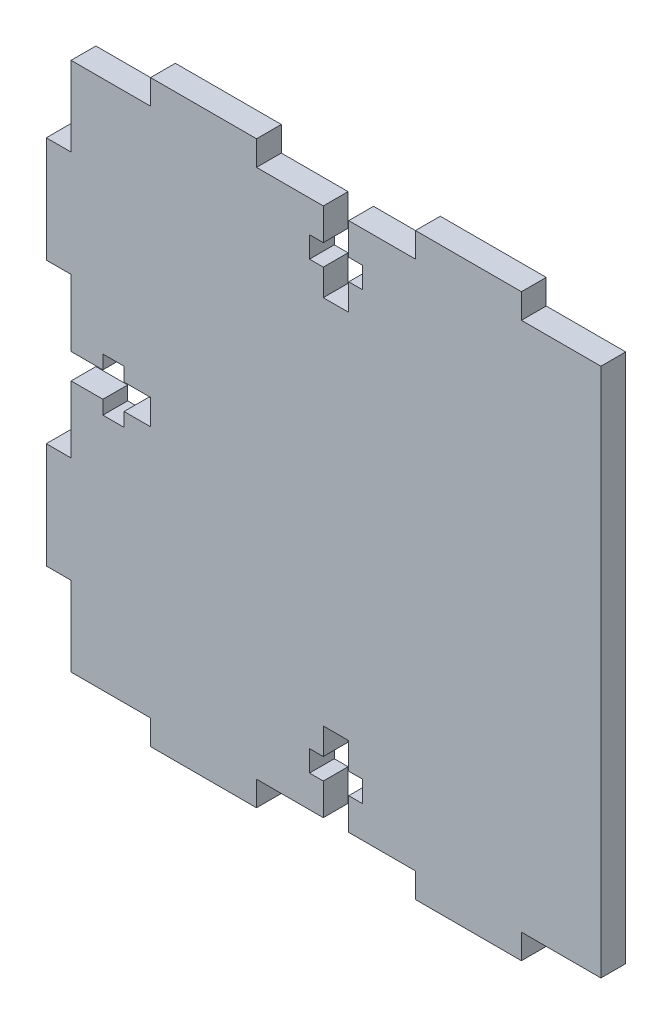
SolidWorks part; units mm, degrees
ref_plane "Front Plane" through (0, 0, 0) normal (0, 0, 1) x (1, 0, 0)
ref_plane "Top Plane" through (0, 0, 0) normal (0, 1, 0) x (1, 0, 0)
ref_plane "Right Plane" through (0, 0, 0) normal (1, 0, 0) x (0, 0, -1)
sketch "Sketch1" plane through (0, 0, 0) normal (0, 0, 1) x (1, 0, 0)
  line L1 (-31.75, -31.75) -> (31.75, -31.75)
  line L2 (-31.75, -31.75) -> (-31.75, 31.75)
  line L3 (-31.75, 31.75) -> (31.75, 31.75)
  line L4 (31.75, -31.75) -> (31.75, 31.75)
  line L5 (-31.75, -31.75) -> (31.75, 31.75) construction
  line L6 (-31.75, 31.75) -> (31.75, -31.75) construction
  point P0 (0, 0)
  dimension "D1" = 63.5
  dimension "D2" = 63.5
extrude "Boss-Extrude1" add sketch "Sketch1" along normal mid plane 2.9718
sketch "Sketch2" plane through (0, 0, 1.4859) normal (0, 0, 1) x (1, 0, 0)
  line L1 (0, 0) -> (39.6082, 0) construction
  line L13 (-31.75, -31.75) -> (31.75, -31.75) construction
  line L14 (-31.75, 31.75) -> (-31.75, -31.75) construction
  point P17 (0.5861, 0)
  line B0 (-1.524, -31.75) -> (-1.524, -27.94)
  line B1 (-1.524, -27.94) -> (-3.175, -27.94)
  line B2 (-3.175, -27.94) -> (-3.175, -25.4)
  line B3 (-3.175, -25.4) -> (-1.524, -25.4)
  line B4 (-1.524, -25.4) -> (-1.524, -22.225)
  line B5 (-1.524, -22.225) -> (1.524, -22.225)
  line B6 (1.524, -22.225) -> (1.524, -25.4)
  line B7 (1.524, -25.4) -> (3.175, -25.4)
  line B8 (3.175, -25.4) -> (3.175, -27.94)
  line B9 (3.175, -27.94) -> (1.524, -27.94)
  line B10 (1.524, -27.94) -> (1.524, -31.75)
  line B11 (1.524, -31.75) -> (-1.524, -31.75)
  line B12 (-31.75, 1.524) -> (-27.94, 1.524)
  line B13 (-27.94, 1.524) -> (-27.94, 3.175)
  line B14 (-27.94, 3.175) -> (-25.4, 3.175)
  line B15 (-25.4, 3.175) -> (-25.4, 1.524)
  line B16 (-25.4, 1.524) -> (-22.225, 1.524)
  line B17 (-22.225, 1.524) -> (-22.225, -1.524)
  line B18 (-22.225, -1.524) -> (-25.4, -1.524)
  line B19 (-25.4, -1.524) -> (-25.4, -3.175)
  line B20 (-25.4, -3.175) -> (-27.94, -3.175)
  line B21 (-27.94, -3.175) -> (-27.94, -1.524)
  line B22 (-27.94, -1.524) -> (-31.75, -1.524)
  line B23 (-31.75, -1.524) -> (-31.75, 1.524)
  line B24 (-1.524, 31.75) -> (-1.524, 27.94)
  line B25 (-1.524, 27.94) -> (-3.175, 27.94)
  line B26 (-3.175, 27.94) -> (-3.175, 25.4)
  line B27 (-3.175, 25.4) -> (-1.524, 25.4)
  line B28 (-1.524, 25.4) -> (-1.524, 22.225)
  line B29 (-1.524, 22.225) -> (1.524, 22.225)
  line B30 (1.524, 22.225) -> (1.524, 25.4)
  line B31 (1.524, 25.4) -> (3.175, 25.4)
  line B32 (3.175, 25.4) -> (3.175, 27.94)
  line B33 (3.175, 27.94) -> (1.524, 27.94)
  line B34 (1.524, 27.94) -> (1.524, 31.75)
  line B35 (1.524, 31.75) -> (-1.524, 31.75)
sketch_block_instance "Block1-1"
sketch_block "Block1" parameters "D1"=3.048, "D2"=2.54, "D3"=6.35, "D4"=3.048, "D5"=1.651
sketch_block_instance "Block1-4"
sketch_block_instance "Block1-8"
extrude "Cut-Extrude1" cut sketch "Sketch2" against normal through all
sketch "Sketch3" plane through (0, 0, 1.4859) normal (0, 0, 1) x (1, 0, 0)
  line L0 (-31.75, -31.75) -> (-1.524, -31.75) construction
  line L1 (-22.225, -31.75) -> (-9.525, -31.75)
  line L2 (-22.225, -31.75) -> (-22.225, -34.7218)
  line L3 (-22.225, -34.7218) -> (-9.525, -34.7218)
  line L4 (-9.525, -31.75) -> (-9.525, -34.7218)
  line L5 (9.525, -31.75) -> (9.525, -34.7218)
  line L6 (9.525, -31.75) -> (22.225, -31.75)
  line L7 (22.225, -31.75) -> (22.225, -34.7218)
  line L8 (9.525, -34.7218) -> (22.225, -34.7218)
  line L9 (-22.225, -31.75) -> (9.525, -31.75) construction
  line L10 (-31.75, 22.225) -> (-31.75, 9.525)
  line L11 (-31.75, 22.225) -> (-34.7218, 22.225)
  line L12 (-34.7218, 22.225) -> (-34.7218, 9.525)
  line L13 (-31.75, 9.525) -> (-34.7218, 9.525)
  line L14 (-31.75, -9.525) -> (-34.7218, -9.525)
  line L15 (-31.75, -9.525) -> (-31.75, -22.225)
  line L16 (-31.75, -22.225) -> (-34.7218, -22.225)
  line L17 (-34.7218, -9.525) -> (-34.7218, -22.225)
  line L18 (-31.75, 22.225) -> (-31.75, -9.525) construction
  line L19 (22.225, 31.75) -> (9.525, 31.75)
  line L20 (22.225, 31.75) -> (22.225, 34.7218)
  line L21 (22.225, 34.7218) -> (9.525, 34.7218)
  line L22 (9.525, 31.75) -> (9.525, 34.7218)
  line L23 (-9.525, 31.75) -> (-9.525, 34.7218)
  line L24 (-9.525, 31.75) -> (-22.225, 31.75)
  line L25 (-22.225, 31.75) -> (-22.225, 34.7218)
  line L26 (-9.525, 34.7218) -> (-22.225, 34.7218)
  line L27 (22.225, 31.75) -> (-9.525, 31.75) construction
  line L28 (0, 0) -> (-9.525, -31.75) construction
  line L29 (0, 0) -> (-31.75, 9.525) construction
  point P6 (-15.875, -34.7218)
  point P21 (-34.7218, 15.875)
  point P32 (15.875, 34.7218)
  dimension "D1" = 2.9718
  dimension "D2" = 12.7
  dimension "D3" = 15.875
  dimension "D4" = 31.75
  dimension "D6" = 90
  dimension "D5" = 3
extrude "Boss-Extrude2" add sketch "Sketch3" against normal blind 2.9718
